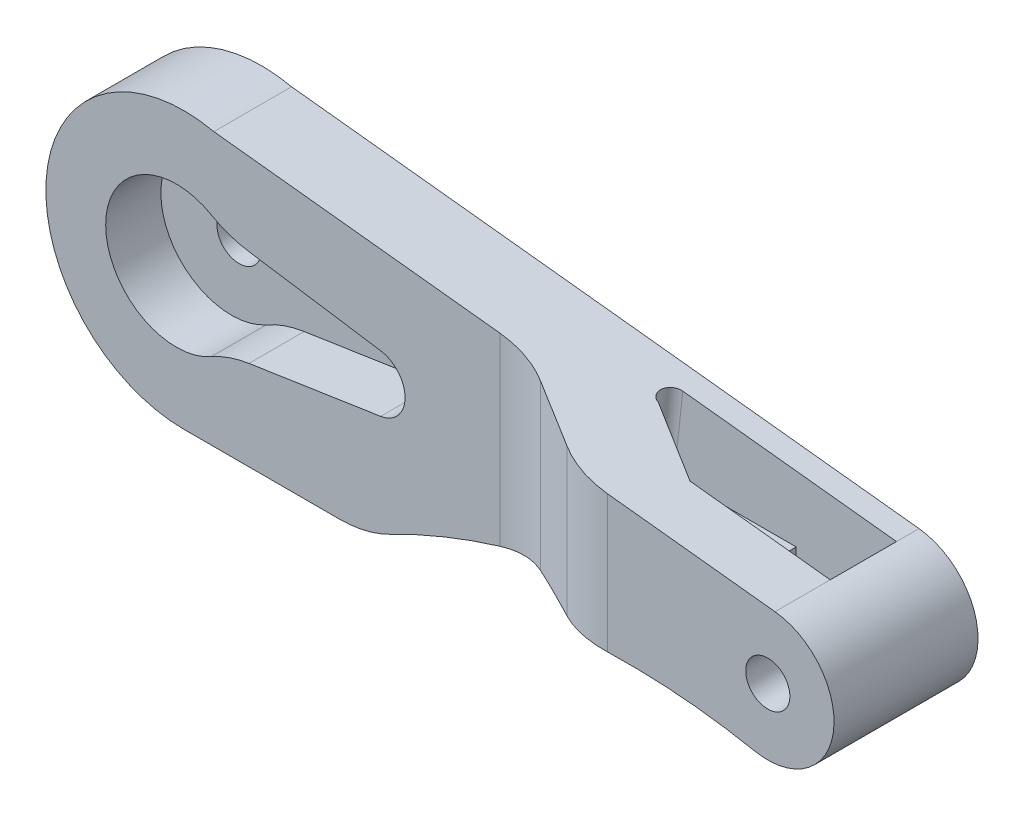
SolidWorks part; units mm, degrees
ref_plane "前视基准面" through (0, 0, 0) normal (0, 0, 1) x (1, 0, 0)
ref_plane "上视基准面" through (0, 0, 0) normal (0, 1, 0) x (1, 0, 0)
ref_plane "右视基准面" through (0, 0, 0) normal (1, 0, 0) x (0, 0, -1)
sketch "草图1" plane through (0, 0, 0) normal (0, 0, 1) x (1, 0, 0)
  line L0 (2.7117, 12.2023) -> (59.5381, 5.9642)
  line L1 (0, -12.5) -> (16.63, -12.5)
  arc A0 (2.7117, 12.2023) -> (0, -12.5) centre (0, 0) ccw
  arc A1 (57.7229, -5.8867) -> (16.63, -12.5) centre (46.1181, -64.7537) ccw
  arc A2 (57.7229, -5.8867) -> (59.5381, 5.9642) centre (58.8833, 0) ccw
  point P1 (60.2802, 5.848)
  point P8 (0, 0)
  point P9 (67.6155, -68.7749)
  point P11 (0, 12.5)
  point P12 (0, 0)
  point P13 (99.8117, -4.0059)
  point P14 (4.1354, 12.4996)
  point P15 (0, -12.5)
  point P16 (0, -12.5)
  point P17 (0, 12.5714)
  point P18 (0, 12.5714)
  point P19 (0, 12.5714)
  point P20 (0, 0)
  point P21 (0, 0)
  point P23 (90.3544, 10.1289)
  point P24 (36.7434, -12.5)
  point P25 (0, 0)
  point P26 (0, 0)
  point P27 (0, -16.6718)
  point P28 (0, 0)
  point P29 (0, 12.5)
  point P30 (0, 0)
  point P31 (0, -12.5)
  point P32 (61.2226, 0)
  point P33 (59.8119, 0)
  point P34 (0, 0)
  point P35 (59.9962, -5.9694)
  point P36 (60.2802, 6)
  point P37 (60.2802, 5.848)
  point P38 (60.2802, 6.1738)
  point P40 (59.9262, 5.9854)
  point P41 (59.5381, -6)
  dimension "D1" = 25
  dimension "D2" = 120
  dimension "D3" = 13.42
  dimension "D4" = 12
  dimension "D5" = 16.63
extrude "凸台-拉伸1" add sketch "草图1" along normal blind 4.04
sketch "草图2" plane through (0, 0, 0) normal (0, 0, -1) x (-1, 0, 0)
  line L2 (-16.63, -12.5) -> (0, -12.5)
  line L3 (-2.7117, 12.2023) -> (-59.5381, 5.9642)
  line L4 (-16.63, -12.5) -> (0, -12.5)
  line L5 (-2.7117, 12.2023) -> (-59.5381, 5.9642)
  arc A3 (-59.5381, 5.9642) -> (-57.7229, -5.8867) centre (-58.8833, 0) ccw
  arc A4 (-16.63, -12.5) -> (-57.7229, -5.8867) centre (-46.1181, -64.7537) ccw
  arc A5 (0, -12.5) -> (-2.7117, 12.2023) centre (0, 0) ccw
  arc A6 (-59.5381, 5.9642) -> (-57.7229, -5.8867) centre (-58.8833, 0) ccw
  arc A7 (-16.63, -12.5) -> (-57.7229, -5.8867) centre (-46.1181, -64.7537) ccw
  arc A8 (0, -12.5) -> (-2.7117, 12.2023) centre (0, 0) ccw
  dimension "D1" = 0
extrude "凸台-拉伸2" add sketch "草图2" along normal blind 3
sketch "草图3" plane through (0, 0, 4.04) normal (0, 0, 1) x (1, 0, 0)
  line L0 (31.3029, 9.0637) -> (59.5381, 5.9642)
  line L1 (59.5381, 5.9642) -> (2.7117, 12.2023) construction
  line L2 (31.3029, 9.0637) -> (31.3029, -6.6116)
  arc A0 (57.7229, -5.8867) -> (16.63, -12.5) centre (46.1181, -64.7537) ccw construction
  arc A1 (57.7229, -5.8867) -> (59.5381, 5.9642) centre (58.8833, 0) ccw construction
  arc A2 (57.7229, -5.8867) -> (31.3029, -6.6116) centre (46.1181, -64.7537) ccw
  arc A3 (57.7229, -5.8867) -> (59.5381, 5.9642) centre (58.8833, 0) ccw
  dimension "D1" = 26.42
extrude "凸台-拉伸3" add sketch "草图3" along normal blind 6
sketch "草图4" plane through (1.3559, 12.3512, 0) normal (0.1091, 0.994, 0) x (0.994, -0.1091, 0)
  line L0 (45.7617, -5.04) -> (58.5317, -5.04)
  line L1 (58.5317, -5.04) -> (58.5317, 0.96)
  line L2 (58.5317, 0.96) -> (39.0617, 0.96)
  line L3 (45.7617, -5.04) -> (38.8335, -1.04)
  line L4 (58.5317, -10.04) -> (30.1269, -10.04) construction
  line L5 (58.5317, -10.04) -> (58.5317, 3) construction
  arc A0 (39.0617, 0.96) -> (38.8335, -1.04) centre (39.0617, -0.053) ccw
  point P10 (0, 0)
  point P13 (38.5134, -1.04)
  dimension "D1" = 5
  dimension "D2" = 9
  dimension "D3" = 6
  dimension "D4" = 19.47
  dimension "D5" = 0
  dimension "D6" = 150
  dimension "D7" = 12.77
extrude "切除-拉伸1" cut sketch "草图4" against normal through all
sketch "草图5" plane through (0, 0, 4.04) normal (0, 0, 1) x (1, 0, 0)
  line L0 (3.63, 4.7275) -> (17.8235, 2.5705)
  line L1 (3.63, -4.7275) -> (17.8235, -2.5705)
  line L2 (0, -12.5) -> (16.63, -12.5) construction
  line L3 (31.3029, 9.0637) -> (2.7117, 12.2023) construction
  line L4 (31.3029, 9.0637) -> (31.3029, -6.6116) construction
  arc A0 (17.8235, -2.5705) -> (17.8235, 2.5705) centre (17.4329, 0) ccw
  arc A1 (3.63, 4.7275) -> (3.63, -4.7275) centre (-0.684, 0) ccw
  point P4 (-0.6773, 7.1294)
  point P6 (-0.684, 0)
  point P8 (2.0518, -5.7858)
  point P9 (0, 0)
  point P10 (0, 0)
  point P11 (0, 0)
  point P12 (0, 0)
  point P13 (0, 0)
  point P16 (0, 0)
  point P17 (0, 0)
  point P18 (7.7082, 5.866)
  point P21 (0, 0)
  point P22 (15.7064, 2.396)
  point P23 (0, 0)
  point P24 (0, 0)
  point P27 (0, 0)
  dimension "D1" = 5.2
  dimension "D2" = 12.8
  dimension "D4" = 12.5
  dimension "D5" = 12.5
  dimension "D6" = 7.33
  dimension "D7" = 13.87
extrude "切除-拉伸2" cut sketch "草图5" against normal blind 5
draft "拔模1" type of draft neutral plane draft angle 60 faces to draft 1 face at (31.3029, 1.2261, 7.04) neutral plane through (58.8833, 0, 4.04) neutral plane normal (0, 0, 1) parameters "D1"=60
sketch "草图6" plane through (0, 0, 10.04) normal (0, 0, 1) x (1, 0, 0)
  circle A2 centre (58.8833, 0) radius 2
extrude "切除-拉伸3" cut sketch "草图6" against normal up to surface (13.04 mm away) up to face at (25.6827, -1.6954, -3)
sketch "草图7" plane through (0, 0, -0.96) normal (0, 0, 1) x (1, 0, 0)
  circle A0 centre (0, 0) radius 2.0022
extrude "切除-拉伸4" cut sketch "草图7" against normal blind 5
sketch "草图8" plane through (0, 0, 0) normal (0, 1, 0) x (1, 0, 0)
  line L1 (46.8443, -5.04) -> (59.5381, -5.04) construction
  line L2 (50.4543, -5.04) -> (50.4543, 0.96)
  line L3 (59.5381, 0.96) -> (40.1843, 0.96) construction
rib "筋1" sketch "草图8" sketch "草图8" thickness 2 extrusion direction parallel to sketch draft on no parameters "D1"=2
fillet "圆角1" radius 10 1 edges at (16.63, -12.5, 0.52)
fillet "圆角2" radius 10 4 edges at (31.3029, 1.2261, 4.04) (41.6952, 1.503, 10.04) (3.63, 4.7275, 1.54) (3.63, -4.7275, 1.54)
